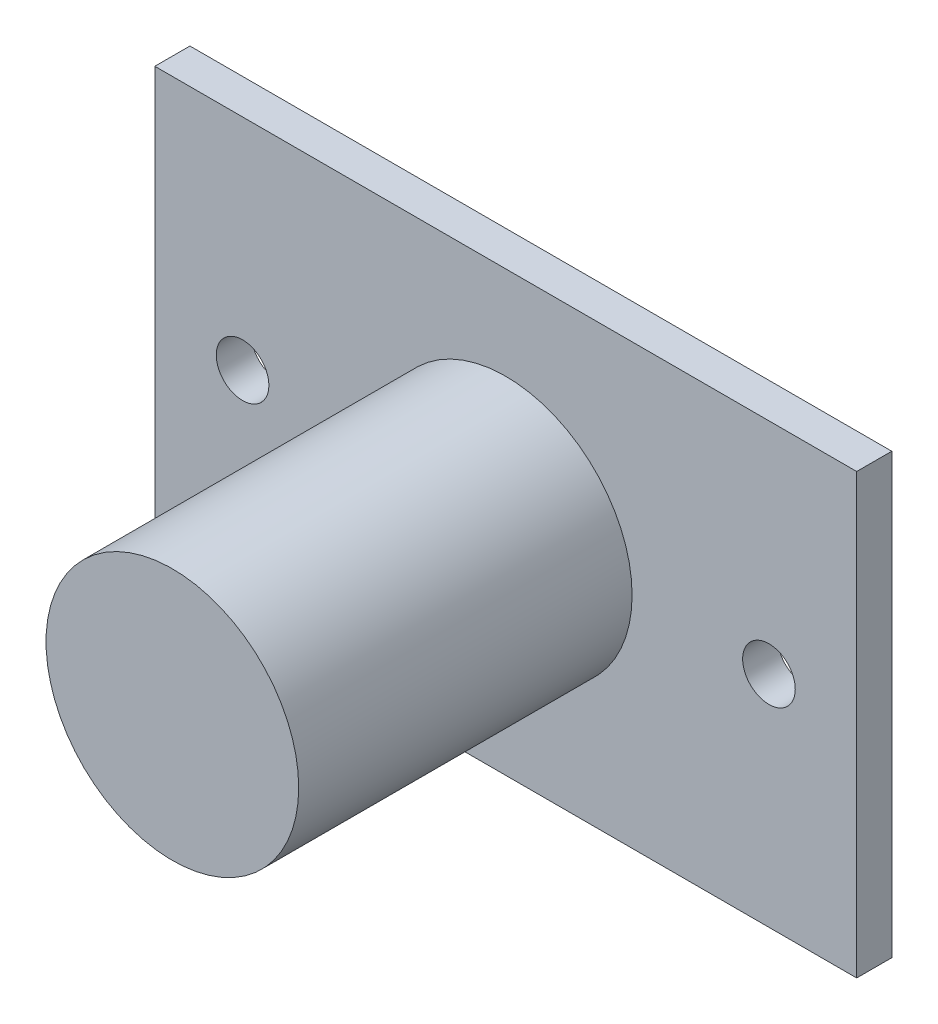
SolidWorks part; units mm, degrees
ref_plane "Front Plane" through (0, 0, 0) normal (0, 0, 1) x (1, 0, 0)
ref_plane "Top Plane" through (0, 0, 0) normal (0, 1, 0) x (1, 0, 0)
ref_plane "Right Plane" through (0, 0, 0) normal (1, 0, 0) x (0, 0, -1)
sketch "Sketch1" plane through (0, 0, 0) normal (0, 0, 1) x (1, 0, 0)
  line L1 (20, 12.5) -> (-20, 12.5)
  line L2 (20, 12.5) -> (20, -12.5)
  line L3 (20, -12.5) -> (-20, -12.5)
  line L4 (-20, 12.5) -> (-20, -12.5)
  line L5 (20, 12.5) -> (-20, -12.5) construction
  line L6 (20, -12.5) -> (-20, 12.5) construction
  circle A0 centre (15, 0) radius 1.5
  circle A1 centre (-15, 0) radius 1.5
  point P0 (0, 0)
  dimension "D3" = 3
  dimension "D4" = 3
  dimension "D5" = 30
  dimension "D6" = 15
  dimension "D1" = 40
  dimension "D2" = 25
extrude "Boss-Extrude1" add sketch "Sketch1" along normal blind 2
sketch "Sketch2" plane through (0, 0, 2) normal (0, 0, 1) x (1, 0, 0)
  circle A0 centre (0, 0) radius 7.2
  dimension "D1" = 14.4
extrude "Boss-Extrude2" add sketch "Sketch2" along normal blind 19
